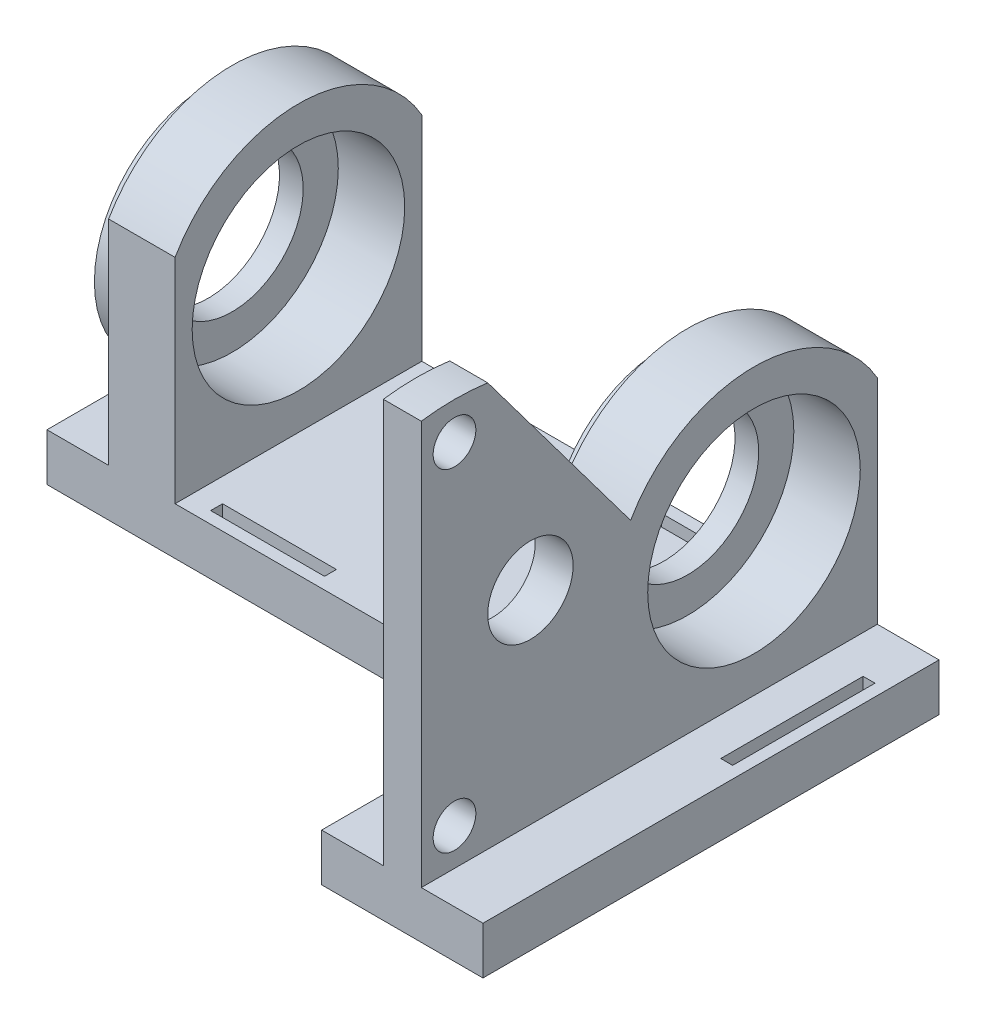
SolidWorks part; units mm, degrees
ref_plane "Front Plane" through (0, 0, 0) normal (0, 0, 1) x (1, 0, 0)
ref_plane "Top Plane" through (0, 0, 0) normal (0, 1, 0) x (1, 0, 0)
ref_plane "Right Plane" through (0, 0, 0) normal (1, 0, 0) x (0, 0, -1)
sketch "Sketch1" plane through (0, 0, 0) normal (0, 1, 0) x (1, 0, 0)
  line L0 (0, 0) -> (20, 0)
  line L1 (0, 0) -> (0, 26)
  line L2 (0, 26) -> (20, 26)
  line L3 (20, 26) -> (20, 0)
  line L4 (0, 26) -> (1.6662, 26)
  line L5 (2.5, 20.5) -> (2.5, 5.5)
  line L6 (20, 26) -> (16.6758, 26)
  line L8 (0, 26) -> (0.8331, 26)
  line L9 (1.25, 20.5) -> (1.25, 5.5)
  line L13 (0, 13) -> (20, 13) construction
  line L16 (2.5, 20.5) -> (1.25, 20.5)
  line L18 (2.5, 5.5) -> (1.25, 5.5)
  line L19 (10, 26) -> (10, 0) construction
  line L28 (14.1758, 26) -> (10, 26)
  dimension "D1" = 20
  dimension "D2" = 26
  dimension "D3" = 15
  dimension "D4" = 1.25
  dimension "D5" = 1.25
  dimension "D6" = 5.5
extrude "Boss-Extrude5" add sketch "Sketch1" along normal blind 5
sketch "Sketch3" plane through (0, 5, 0) normal (0, 1, 0) x (1, 0, 0)
  line L0 (2.5, 20.5) -> (2.5, 5.5) construction
  line L5 (6.5, 0) -> (13.5, 0)
  line L6 (6.5, 0) -> (6.5, 26)
  line L7 (6.5, 26) -> (13.5, 26)
  line L8 (13.5, 0) -> (13.5, 26)
  line L9 (6.5, 0) -> (13.5, 26) construction
  line L10 (6.5, 26) -> (13.5, 0) construction
  line L11 (0, 26) -> (20, 26) construction
  point P0 (10, 13)
  dimension "D1" = 7.5
  dimension "D2" = 7
  dimension "D3" = 26
  dimension "D4" = 13
extrude "Boss-Extrude6" add sketch "Sketch3" along normal blind 40
sketch "Sketch5" plane through (13.5, 0, 0) normal (1, 0, 0) x (0, 0, -1)
  line L2 (13, 45) -> (13, 5) construction
  line L3 (0, 45) -> (26, 45) construction
  line L4 (0, 5) -> (26, 5) construction
  line L5 (26, 5) -> (0, 5) construction
  line L6 (0, 27.4833) -> (0, 45)
  line L7 (0, 45) -> (26, 45)
  line L10 (26, 45) -> (26, 27.4833)
  line L16 (26, 45) -> (26, 5) construction
  circle A0 centre (13, 20) radius 11.2
  arc A3 (26, 27.4833) -> (0, 27.4833) centre (13, 20) ccw
  dimension "D1" = 15
  dimension "D2" = 22.4
  dimension "D3" = 30
extrude "Cut-Extrude1" cut sketch "Sketch5" against normal up to next
sketch "Sketch6" plane through (20, 0, 0) normal (1, 0, 0) x (0, 0, -1)
  line L1 (0, 0) -> (26, 0)
  line L2 (0, 0) -> (0, 5)
  line L3 (0, 5) -> (26, 5)
  line L4 (26, 0) -> (26, 5)
extrude "Boss-Extrude8" add sketch "Sketch6" along normal blind 14
mirror "Mirror5" about plane through (34, 0, 0) normal (-1, 0, 0) of "Cut-Extrude1", "Boss-Extrude8", "Boss-Extrude6", "Boss-Extrude5"
sketch "Sketch7" plane through (0, 5, 0) normal (0, 1, 0) x (1, 0, 0)
  line L0 (34, 26) -> (34, 0) construction
  line L5 (13.5, 0) -> (13.5, 26) construction
  line L6 (16, 2.5) -> (28, 2.5)
  line L7 (16, 2.5) -> (16, 1.25)
  line L8 (13.5, 0) -> (54.5, 0) construction
  line L9 (13.5, 0) -> (13.5, 26) construction
  line L10 (13.5, 13) -> (54.5, 13) construction
  line L11 (16, 1.25) -> (28, 1.25)
  line L12 (28, 2.5) -> (28, 1.25)
  line L13 (54.5, 0) -> (54.5, 26) construction
  line L14 (13.5, 26) -> (54.5, 26) construction
  line L15 (40, 2.5) -> (40, 1.25)
  line L16 (52, 1.25) -> (40, 1.25)
  line L17 (52, 2.5) -> (52, 1.25)
  line L18 (52, 2.5) -> (40, 2.5)
  line L19 (52, 23.5) -> (40, 23.5)
  line L20 (52, 23.5) -> (52, 24.75)
  line L21 (52, 24.75) -> (40, 24.75)
  line L22 (40, 23.5) -> (40, 24.75)
  line L23 (28, 23.5) -> (28, 24.75)
  line L24 (16, 24.75) -> (28, 24.75)
  line L25 (16, 23.5) -> (16, 24.75)
  line L26 (16, 23.5) -> (28, 23.5)
  dimension "D1" = 1.25
  dimension "D2" = 12
  dimension "D3" = 1.25
  dimension "D4" = 2.5
sketch "Sketch8" plane through (6.5, 0, 0) normal (-1, 0, 0) x (0, 0, 1)
  circle A0 centre (-13, 20) radius 11.2 construction
  circle A3 centre (-13, 20) radius 12
  circle A4 centre (-13, 20) radius 7.5
  point P4 (-13, 20)
  dimension "D1" = 15
  dimension "D2" = 24
extrude "Boss-Extrude9" add sketch "Sketch8" along normal blind 2.5
sketch "Sketch9" plane through (54.5, 0, 0) normal (-1, 0, 0) x (0, 0, 1)
  circle A0 centre (-13, 20) radius 7.5 construction
  circle A1 centre (-13, 20) radius 12
  circle A2 centre (-13, 20) radius 12
  circle A3 centre (-13, 20) radius 7.5
  dimension "D1" = 0
extrude "Boss-Extrude10" add sketch "Sketch9" along normal blind 2.5
extrude "Cut-Extrude2" cut sketch "Sketch7" against normal blind 10
sketch "Sketch10" plane through (0, 0, 0) normal (0, 0, 1) x (1, 0, 0)
  line L11 (51, 0) -> (68, 0)
  line L12 (51, 5) -> (51, 0)
  line L13 (57.5, 5) -> (51, 5)
  line L14 (57.5, 47.8) -> (57.5, 5)
  line L15 (61.5, 47.8) -> (57.5, 47.8)
  line L16 (61.5, 5) -> (61.5, 47.8)
  line L17 (68, 5) -> (61.5, 5)
  line L18 (68, 0) -> (68, 5)
  dimension "D3" = 4
  dimension "D4" = 42.8
extrude "Boss-Extrude11" add sketch "Sketch10" along normal blind 37.12
sketch "Sketch13" plane through (0, 5, 0) normal (0, 1, 0) x (1, 0, 0)
  line L0 (28, 2.5) -> (40, 2.5)
  line L1 (34, 2.5) -> (34, 26)
  line L2 (13.5, 26) -> (54.5, 26) construction
ref_plane "Plane2" through (34, 0, 0) normal (1, 0, 0) x (0, 0, -1)
sketch "Sketch14" plane through (61.5, 0, 0) normal (1, 0, 0) x (0, 0, -1)
  line L8 (-15.0569, 39.9524) -> (-15.0569, 43.897) construction
  line L9 (-22.0569, 39.9524) -> (-22.0569, 43.897) construction
  line L10 (-22.0569, 12.8415) -> (-22.0569, 8.897) construction
  line L11 (-15.0569, 12.8415) -> (-15.0569, 8.897) construction
  line L15 (-37.12, 5) -> (-37.12, 47.8) construction
  line L16 (-37.12, 39.9524) -> (-37.12, 51.8324)
  line L17 (-37.12, 51.8324) -> (0, 51.8324)
  line L18 (0, 51.8324) -> (0, 39.9524)
  arc A10 (-15.0569, 39.9524) -> (-15.0569, 12.8415) centre (-18.5569, 26.397) cw construction
  arc A11 (-22.0569, 43.897) -> (-15.0569, 43.897) centre (-18.5569, 43.897) cw construction
  arc A12 (-22.0569, 8.897) -> (-15.0569, 8.897) centre (-18.5569, 8.897) ccw construction
  arc A13 (-22.0569, 12.8415) -> (-22.0569, 39.9524) centre (-18.5569, 26.397) cw construction
  circle A14 centre (13, 20) radius 24.41 construction
  circle A16 centre (-18.5569, 43.897) radius 2.25
  circle A17 centre (-10.5569, 26.397) radius 4.5
  circle A18 centre (-18.5569, 43.897) radius 2.25
  circle A19 centre (-18.5569, 8.897) radius 2.25
  arc A20 (-37.12, 39.9524) -> (0, 39.9524) centre (-18.56, 21.9284) cw
  point P0 (-10.5569, 26.397)
  point P50 (-10.5569, 26.397)
  line M10 (0, 27.4833) -> (0, 47.8)
  line M11 (0, 47.8) -> (-37.12, 47.8)
  line M12 (-37.12, 47.8) -> (-37.12, 5)
  dimension "D1" = 48.82
extrude "Cut-Extrude4" cut sketch "Sketch14" against normal blind 10 contours L18 L17 L16 M11 | A20 M11 M10 | A20 M12 M11 | A16 | A17 | A19
sketch "Sketch15" plane through (57.5, 0, 0) normal (-1, 0, 0) x (0, 0, 1)
  line L3 (37.12, 0) -> (37.12, 5) construction
  line L4 (37.12, 0) -> (0, 0) construction
  line L5 (37.12, 5) -> (37.12, 39.9524) construction
  line L6 (0, 39.9524) -> (0, 27.4833) construction
  line L15 (37.12, 0) -> (37.12, 5)
  line L20 (37.12, 5) -> (37.12, 39.9524)
  line L21 (0, 39.9524) -> (0, 27.4833)
  line L23 (22.0569, 47.5626) -> (22.0569, 0)
  line L25 (22.0569, 0) -> (37.12, 0)
  line L26 (15.0569, 47.5617) -> (0, 27.4833)
  arc A0 (37.12, 39.9524) -> (0, 39.9524) centre (18.56, 21.9284) ccw construction
  arc A1 (37.12, 39.9524) -> (22.0569, 47.5626) centre (18.56, 21.9284) ccw
  circle A3 centre (18.5569, 43.897) radius 2.25 construction
  arc A4 (15.0569, 47.5617) -> (0, 39.9524) centre (18.56, 21.9284) ccw
  point P1 (22.0569, 0)
  point P15 (0, 0)
  point P16 (0, 26.9529)
  dimension "D1" = 3.5
  dimension "D2" = 3.5
extrude "Cut-Extrude5" cut sketch "Sketch15" against normal up to surface and the other way up to surface up to face at (68, 2.5, 5.56) other way up to face at (51, 2.5, 18.56)
